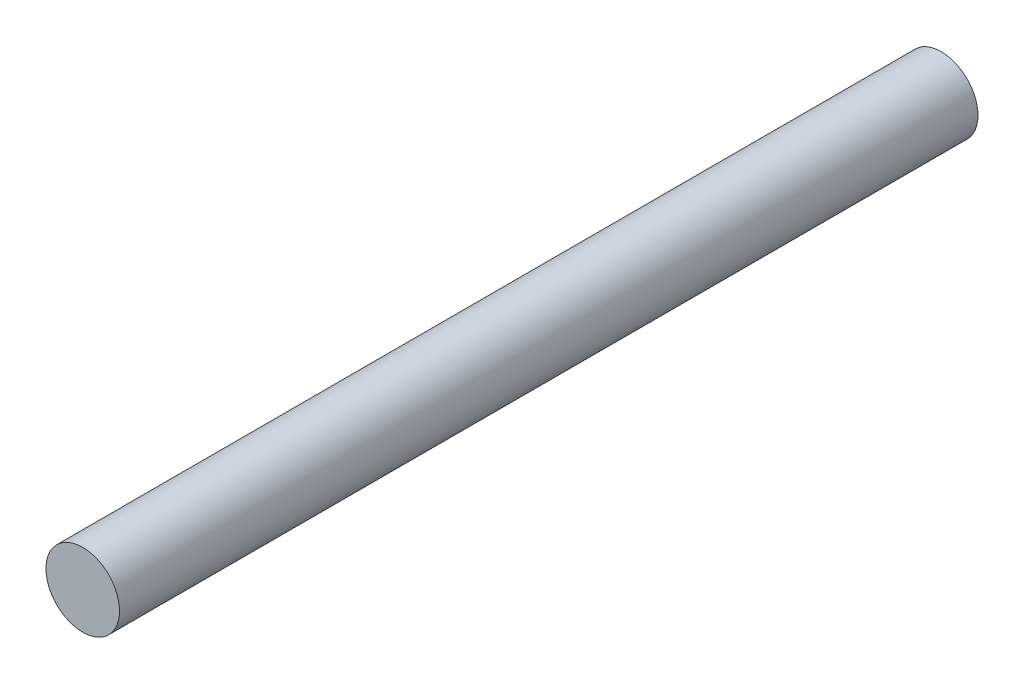
SolidWorks part; units mm, degrees
ref_plane "Alzado" through (0, 0, 0) normal (0, 0, 1) x (1, 0, 0)
ref_plane "Planta" through (0, 0, 0) normal (0, 1, 0) x (1, 0, 0)
ref_plane "Vista lateral" through (0, 0, 0) normal (1, 0, 0) x (0, 0, -1)
sketch "Croquis1" plane through (0, 0, 0) normal (0, 0, 1) x (1, 0, 0)
  circle A0 centre (0, 0) radius 1.5
  dimension "D1" = 3
extrude "Saliente-Extruir1" add sketch "Croquis1" along normal blind 35
